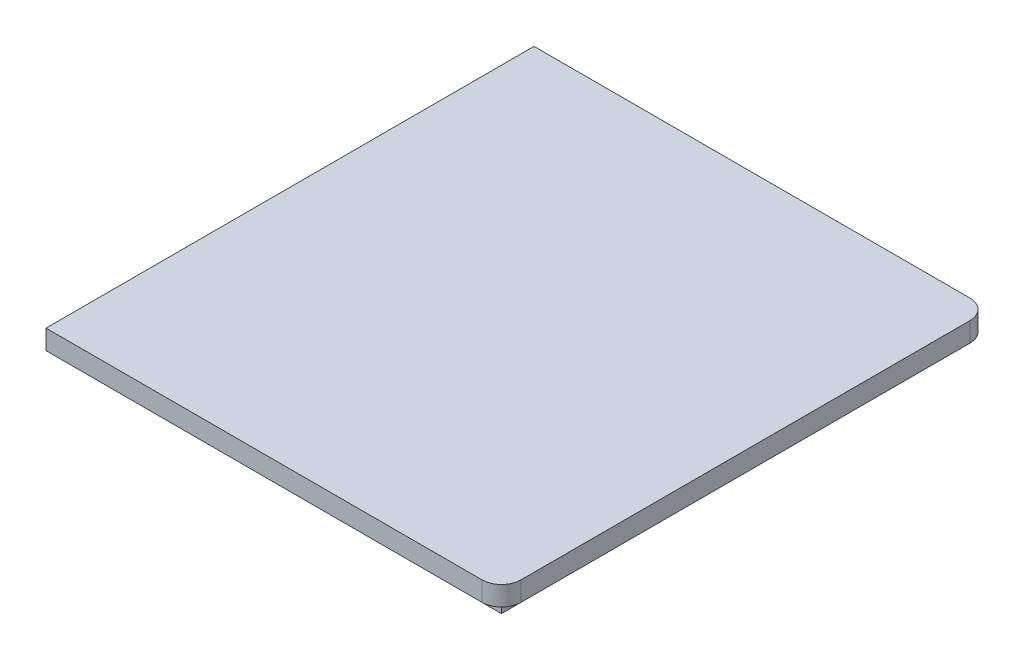
SolidWorks part; units mm, degrees
ref_plane "Front Plane" through (0, 0, 0) normal (0, 0, 1) x (1, 0, 0)
ref_plane "Top Plane" through (0, 0, 0) normal (0, 1, 0) x (1, 0, 0)
ref_plane "Right Plane" through (0, 0, 0) normal (1, 0, 0) x (0, 0, -1)
sketch "Sketch1" plane through (0, 0, 0) normal (0, 1, 0) x (1, 0, 0)
  line L1 (-35, 37.5) -> (35, 37.5)
  line L2 (-35, 37.5) -> (-35, -37.5)
  line L3 (-35, -37.5) -> (35, -37.5)
  line L4 (35, 37.5) -> (35, -37.5)
  line L5 (-35, 37.5) -> (35, -37.5) construction
  line L6 (-35, -37.5) -> (35, 37.5) construction
  point P0 (0, 0)
  dimension "D1" = 75
  dimension "D2" = 70
extrude "Boss-Extrude1" add sketch "Sketch1" along normal blind 3 contours L2 L3 L4 L1
sketch "Sketch2" plane through (0, 0, 0) normal (0, -1, 0) x (1, 0, 0)
  line L14 (32, 34.5) -> (-32, 34.5)
  line L15 (32, -34.5) -> (32, 34.5)
  line L16 (-32, -34.5) -> (32, -34.5)
  line L17 (-32, 34.5) -> (-32, -34.5)
  line L18 (32, 34.5) -> (-32, 34.5)
  line L19 (32, -34.5) -> (32, 34.5)
  line L20 (-32, -34.5) -> (32, -34.5)
  line L21 (-32, 34.5) -> (-32, -34.5)
  dimension "D1" = 3
extrude "Boss-Extrude2" add sketch "Sketch2" along normal blind 3
fillet "Fillet1" radius 3 2 edges at (35, 1.5, 37.5) (35, 1.5, -37.5)
